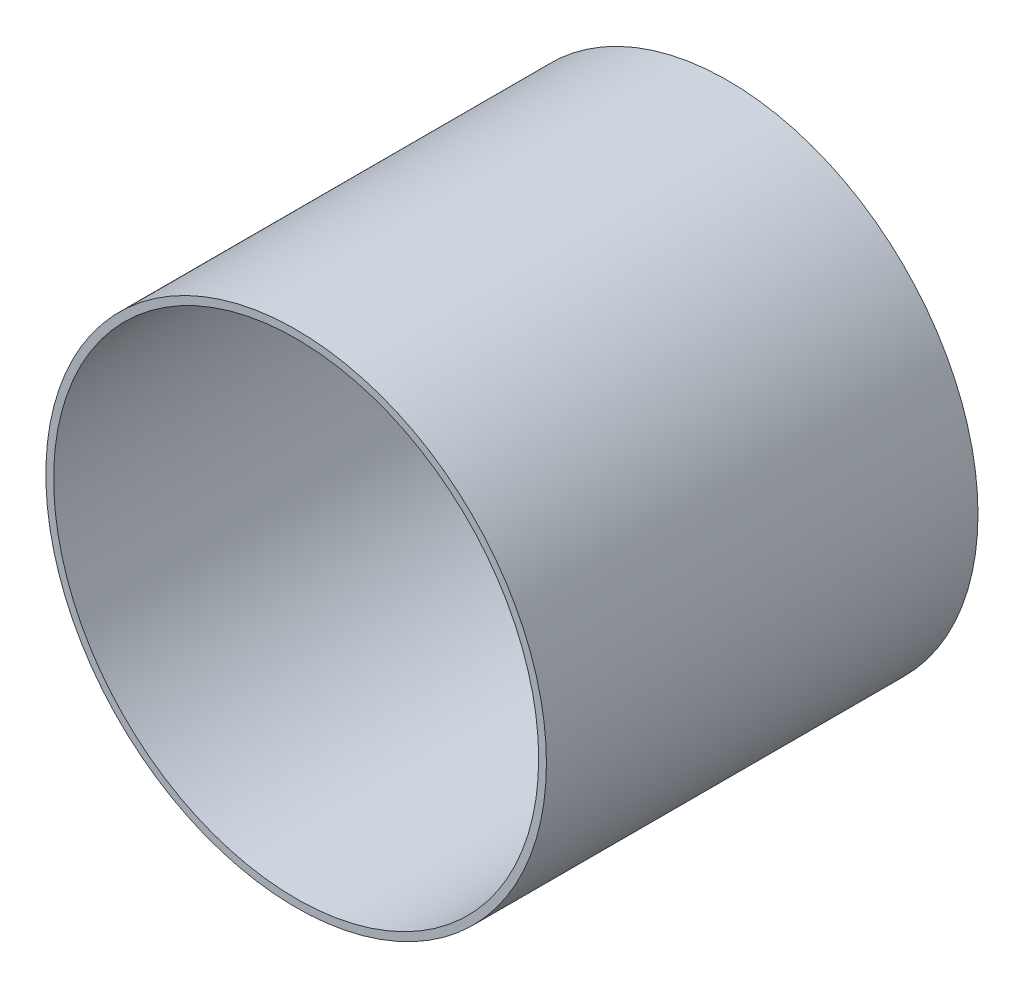
SolidWorks part; units mm, degrees
ref_plane "Front Plane" through (0, 0, 0) normal (0, 0, 1) x (1, 0, 0)
ref_plane "Top Plane" through (0, 0, 0) normal (0, 1, 0) x (1, 0, 0)
ref_plane "Right Plane" through (0, 0, 0) normal (1, 0, 0) x (0, 0, -1)
sketch "Sketch1" plane through (0, 0, 0) normal (0, 0, 1) x (1, 0, 0)
  circle A0 centre (0, 0) radius 14.05
  circle A1 centre (0, 0) radius 14.5
  dimension "D1" = 29
  dimension "D2" = 28.1
extrude "Boss-Extrude1" add sketch "Sketch1" along normal blind 25
